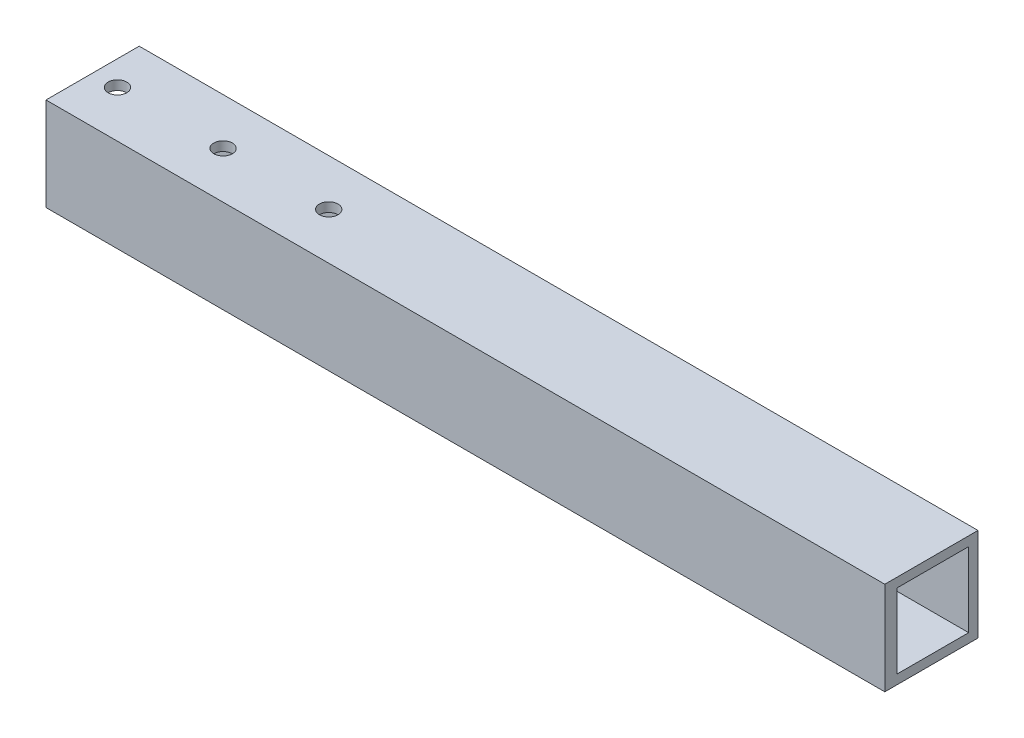
SolidWorks part; units mm, degrees
material "6061 合金"
ref_plane "前视基准面" through (0, 0, 0) normal (0, 0, 1) x (1, 0, 0)
ref_plane "上视基准面" through (0, 0, 0) normal (0, 1, 0) x (1, 0, 0)
ref_plane "右视基准面" through (0, 0, 0) normal (1, 0, 0) x (0, 0, -1)
sketch3d "3D草图1"
  line L0 (0, 0, 0) -> (135, 0, 0)
  dimension "D1" = 135
other "方形管 15 ×15× 1.5(1)"
ref_plane "基准面1" through (0, 0, 0) normal (1, 0, 0) x (0, 0, -1)
sketch "Sketch1" plane through (0, 0, 0) normal (1, 0, 0) x (0, 0, -1)
  line L0 (-4, -6) -> (4, -6)
  line L1 (-5.5, -3.5) -> (-5.5, 3.5)
  line L2 (3.5, 6) -> (-3.5, 6)
  line L3 (6, 3.5) -> (6, -3.5)
  line L4 (-6, -7.5) -> (6, -7.5)
  line L5 (-7.5, -6) -> (-7.5, 6)
  line L6 (6, 7.5) -> (-6, 7.5)
  line L7 (7.5, 6) -> (7.5, -6)
  line L8 (-5.5, 3.5) -> (-5.5, 6)
  line L9 (-5.5, 6) -> (-3.5, 6)
  line L10 (-7.5, 6) -> (-7.5, 7.5)
  line L11 (-7.5, 7.5) -> (-6, 7.5)
  line L12 (6, 7.5) -> (7.5, 7.5)
  line L13 (7.5, 7.5) -> (7.5, 6)
  line L14 (3.5, 6) -> (6, 6)
  line L15 (6, 6) -> (6, 3.5)
  line L16 (4, -6) -> (6, -6)
  line L17 (6, -6) -> (6, -3.5)
  line L18 (7.5, -6) -> (7.5, -7.5)
  line L19 (7.5, -7.5) -> (6, -7.5)
  line L20 (-5.5, -3.5) -> (-5.5, -6)
  line L21 (-5.5, -6) -> (-4, -6)
  line L22 (-7.5, -6) -> (-7.5, -7.5)
  line L23 (-7.5, -7.5) -> (-6, -7.5)
  line L24 (0, 7.5) -> (0, -7.5) construction
  line L25 (-7.5, 0) -> (7.5, 0) construction
  point P0 (-7.5, 0)
  point P1 (7.5, 0)
  point P2 (0, 7.5)
  point P3 (0, -7.5)
  point P4 (0, 0)
  point P5 (-7.5, -7.5)
  point P6 (7.5, -7.5)
  point P7 (7.5, 7.5)
  point P8 (-7.5, 7.5)
  point P38 (6, 0)
  point P39 (-5.5, 0)
  point P40 (0, 6)
  point P41 (0, -6)
  point P42 (0, 0)
  dimension "D1" = 1.5
  dimension "D2" = 1.5
  dimension "D3" = 1.5
  dimension "D4" = 1.5
  dimension "D5" = 1.5
  dimension "D6" = 12
  dimension "D7" = 1.5
  dimension "D8" = 1.5
  dimension "Thickness" = 2
  dimension "D9" = 1.5
  dimension "D10" = 1.5
sketch "草图4" plane through (0, -7.5, 0) normal (0, -1, 0) x (1, 0, 0)
  line L0 (0, 0) -> (38, 0) construction
  line L1 (0, 7.5) -> (0, -7.5) construction
  circle A0 centre (38, 0) radius 1.5
  circle A1 centre (4, 0) radius 1.5
  circle A2 centre (21, 0) radius 1.5
  dimension "D2" = 3
  dimension "D4" = 17
  dimension "D1" = 4
  dimension "D3" = 17
extrude "切除-拉伸1" cut sketch "草图4" against normal through all
